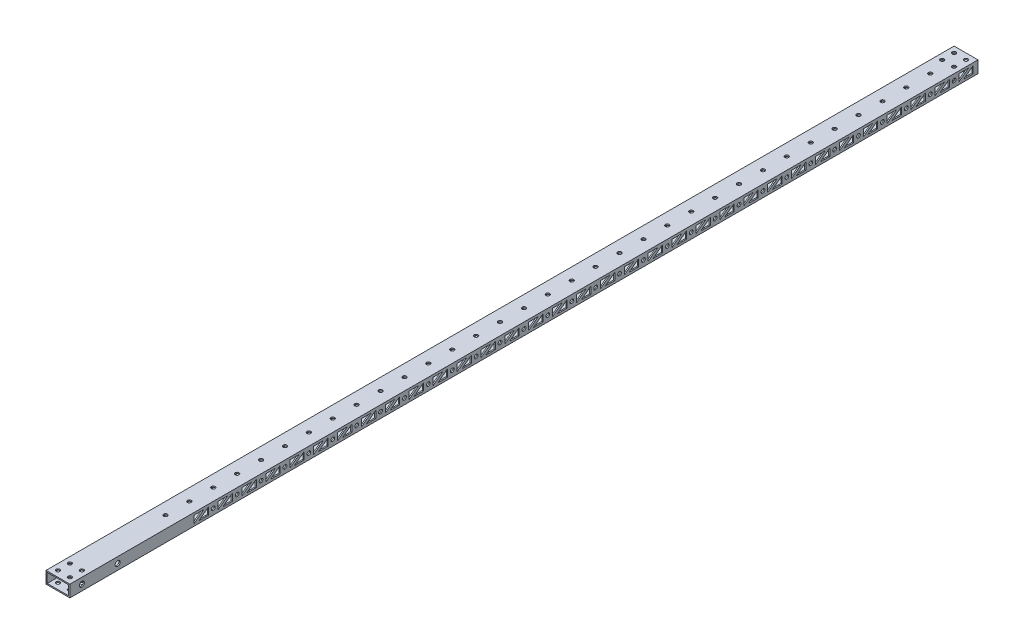
SolidWorks part; units mm, degrees
ref_plane "前视基准面" through (0, 0, 0) normal (0, 0, 1) x (1, 0, 0)
ref_plane "上视基准面" through (0, 0, 0) normal (0, 1, 0) x (1, 0, 0)
ref_plane "右视基准面" through (0, 0, 0) normal (1, 0, 0) x (0, 0, -1)
other "Configuration Table"
sketch "草图1" plane through (0, 0, 0) normal (0, 0, 1) x (1, 0, 0)
  line L1 (0, 0) -> (20, 0)
  line L2 (0, 0) -> (0, -10)
  line L3 (0, -10) -> (20, -10)
  line L4 (20, 0) -> (20, -10)
  dimension "D1" = 20
  dimension "D2" = 10
extrude "拉伸-薄壁1" add sketch "草图1" along normal blind 760 thin
sketch "草图2" plane through (0, -10, 0) normal (0, -1, 0) x (1, 0, 0)
  line L0 (20, 10) -> (0, 10) construction
  line L1 (20, 760) -> (20, 0) construction
  line L2 (0, 760) -> (0, 0) construction
  line L3 (10, 0) -> (10, 10) construction
  line L4 (0, 0) -> (20, 0) construction
  line L5 (10, 10) -> (10, 30) construction
  line L6 (0, 380) -> (20, 380) construction
  line L7 (10, 760) -> (10, 750) construction
  line L8 (20, 750) -> (0, 750) construction
  circle A0 centre (5, 5) radius 1.575
  circle A1 centre (15, 5) radius 1.575
  circle A2 centre (15, 15) radius 1.575
  circle A3 centre (5, 15) radius 1.575
  circle A4 centre (10, 30) radius 1.575
  circle A5 centre (10, 50) radius 1.575
  circle A6 centre (10, 70) radius 1.575
  circle A7 centre (10, 90) radius 1.575
  circle A8 centre (10, 110) radius 1.575
  circle A9 centre (10, 130) radius 1.575
  circle A10 centre (10, 150) radius 1.575
  circle A11 centre (10, 170) radius 1.575
  circle A12 centre (10, 190) radius 1.575
  circle A13 centre (10, 210) radius 1.575
  circle A14 centre (10, 230) radius 1.575
  circle A15 centre (10, 250) radius 1.575
  circle A16 centre (10, 270) radius 1.575
  circle A17 centre (10, 290) radius 1.575
  circle A18 centre (10, 310) radius 1.575
  circle A19 centre (10, 330) radius 1.575
  circle A20 centre (10, 350) radius 1.575
  circle A21 centre (10, 370) radius 1.575
  circle A22 centre (10, 390) radius 1.575
  circle A23 centre (10, 410) radius 1.575
  circle A24 centre (10, 430) radius 1.575
  circle A25 centre (10, 450) radius 1.575
  circle A26 centre (10, 470) radius 1.575
  circle A27 centre (10, 490) radius 1.575
  circle A28 centre (10, 510) radius 1.575
  circle A29 centre (10, 530) radius 1.575
  circle A30 centre (10, 550) radius 1.575
  circle A31 centre (10, 570) radius 1.575
  circle A32 centre (10, 590) radius 1.575
  circle A33 centre (10, 610) radius 1.575
  circle A37 centre (5, 745) radius 1.575
  circle A38 centre (15, 745) radius 1.575
  circle A39 centre (15, 755) radius 1.575
  circle A40 centre (5, 755) radius 1.575
  circle A41 centre (10, 630) radius 1.575
  circle A42 centre (10, 650) radius 1.575
  circle A43 centre (10, 670) radius 1.575
  dimension "D1" = 3.15
  dimension "D5" = 3.15
  dimension "D2" = 5
  dimension "D3" = 5
  dimension "D4" = 10
  dimension "D6" = 20
  dimension "D8" = 20
  dimension "D7" = 33
extrude "切除-拉伸1" cut sketch "草图2" against normal through all
sketch "草图4" plane through (20, 0, 0) normal (1, 0, 0) x (0, 0, -1)
  line L0 (0, -5) -> (-760, -5) construction
  line L1 (0, -10) -> (0, 0) construction
  line L2 (-760, -10) -> (-760, 0) construction
  line L3 (-4, -2) -> (-4, -8)
  line L4 (-4, -8) -> (-12, -8)
  line L5 (-12, -8) -> (-4, -2)
  line L6 (-8, -2) -> (-16, -8)
  line L7 (-16, -8) -> (-16, -2)
  line L8 (-16, -2) -> (-8, -2)
  line L9 (-760, -10) -> (0, -10) construction
  line L10 (-760, 0) -> (0, 0) construction
  line L11 (-24, -2) -> (-24, -8)
  line L12 (-24, -8) -> (-32, -8)
  line L13 (-32, -8) -> (-24, -2)
  line L14 (-36, -2) -> (-28, -2)
  line L15 (-28, -2) -> (-36, -8)
  line L16 (-36, -8) -> (-36, -2)
  line L17 (-44, -2) -> (-44, -8)
  line L18 (-44, -8) -> (-52, -8)
  line L19 (-52, -8) -> (-44, -2)
  line L20 (-56, -2) -> (-48, -2)
  line L21 (-48, -2) -> (-56, -8)
  line L22 (-56, -8) -> (-56, -2)
  line L23 (-64, -2) -> (-64, -8)
  line L24 (-64, -8) -> (-72, -8)
  line L25 (-72, -8) -> (-64, -2)
  line L26 (-76, -2) -> (-68, -2)
  line L27 (-68, -2) -> (-76, -8)
  line L28 (-76, -8) -> (-76, -2)
  line L29 (-84, -2) -> (-84, -8)
  line L30 (-84, -8) -> (-92, -8)
  line L31 (-92, -8) -> (-84, -2)
  line L32 (-96, -2) -> (-88, -2)
  line L33 (-88, -2) -> (-96, -8)
  line L34 (-96, -8) -> (-96, -2)
  line L35 (-104, -2) -> (-104, -8)
  line L36 (-104, -8) -> (-112, -8)
  line L37 (-112, -8) -> (-104, -2)
  line L38 (-116, -2) -> (-108, -2)
  line L39 (-108, -2) -> (-116, -8)
  line L40 (-116, -8) -> (-116, -2)
  line L41 (-124, -2) -> (-124, -8)
  line L42 (-124, -8) -> (-132, -8)
  line L43 (-132, -8) -> (-124, -2)
  line L44 (-136, -2) -> (-128, -2)
  line L45 (-128, -2) -> (-136, -8)
  line L46 (-136, -8) -> (-136, -2)
  line L47 (-144, -2) -> (-144, -8)
  line L48 (-144, -8) -> (-152, -8)
  line L49 (-152, -8) -> (-144, -2)
  line L50 (-156, -2) -> (-148, -2)
  line L51 (-148, -2) -> (-156, -8)
  line L52 (-156, -8) -> (-156, -2)
  line L53 (-164, -2) -> (-164, -8)
  line L54 (-164, -8) -> (-172, -8)
  line L55 (-172, -8) -> (-164, -2)
  line L56 (-176, -2) -> (-168, -2)
  line L57 (-168, -2) -> (-176, -8)
  line L58 (-176, -8) -> (-176, -2)
  line L59 (-184, -2) -> (-184, -8)
  line L60 (-184, -8) -> (-192, -8)
  line L61 (-192, -8) -> (-184, -2)
  line L62 (-196, -2) -> (-188, -2)
  line L63 (-188, -2) -> (-196, -8)
  line L64 (-196, -8) -> (-196, -2)
  line L65 (-204, -2) -> (-204, -8)
  line L66 (-204, -8) -> (-212, -8)
  line L67 (-212, -8) -> (-204, -2)
  line L68 (-216, -2) -> (-208, -2)
  line L69 (-208, -2) -> (-216, -8)
  line L70 (-216, -8) -> (-216, -2)
  line L71 (-224, -2) -> (-224, -8)
  line L72 (-224, -8) -> (-232, -8)
  line L73 (-232, -8) -> (-224, -2)
  line L74 (-236, -2) -> (-228, -2)
  line L75 (-228, -2) -> (-236, -8)
  line L76 (-236, -8) -> (-236, -2)
  line L77 (-244, -2) -> (-244, -8)
  line L78 (-244, -8) -> (-252, -8)
  line L79 (-252, -8) -> (-244, -2)
  line L80 (-256, -2) -> (-248, -2)
  line L81 (-248, -2) -> (-256, -8)
  line L82 (-256, -8) -> (-256, -2)
  line L83 (-264, -2) -> (-264, -8)
  line L84 (-264, -8) -> (-272, -8)
  line L85 (-272, -8) -> (-264, -2)
  line L86 (-276, -2) -> (-268, -2)
  line L87 (-268, -2) -> (-276, -8)
  line L88 (-276, -8) -> (-276, -2)
  line L89 (-284, -2) -> (-284, -8)
  line L90 (-284, -8) -> (-292, -8)
  line L91 (-292, -8) -> (-284, -2)
  line L92 (-296, -2) -> (-288, -2)
  line L93 (-288, -2) -> (-296, -8)
  line L94 (-296, -8) -> (-296, -2)
  line L95 (-304, -2) -> (-304, -8)
  line L96 (-304, -8) -> (-312, -8)
  line L97 (-312, -8) -> (-304, -2)
  line L98 (-316, -2) -> (-308, -2)
  line L99 (-308, -2) -> (-316, -8)
  line L100 (-316, -8) -> (-316, -2)
  line L101 (-324, -2) -> (-324, -8)
  line L102 (-324, -8) -> (-332, -8)
  line L103 (-332, -8) -> (-324, -2)
  line L104 (-336, -2) -> (-328, -2)
  line L105 (-328, -2) -> (-336, -8)
  line L106 (-336, -8) -> (-336, -2)
  line L107 (-344, -2) -> (-344, -8)
  line L108 (-344, -8) -> (-352, -8)
  line L109 (-352, -8) -> (-344, -2)
  line L110 (-356, -2) -> (-348, -2)
  line L111 (-348, -2) -> (-356, -8)
  line L112 (-356, -8) -> (-356, -2)
  line L113 (-364, -2) -> (-364, -8)
  line L114 (-364, -8) -> (-372, -8)
  line L115 (-372, -8) -> (-364, -2)
  line L116 (-376, -2) -> (-368, -2)
  line L117 (-368, -2) -> (-376, -8)
  line L118 (-376, -8) -> (-376, -2)
  line L119 (-384, -2) -> (-384, -8)
  line L120 (-384, -8) -> (-392, -8)
  line L121 (-392, -8) -> (-384, -2)
  line L122 (-396, -2) -> (-388, -2)
  line L123 (-388, -2) -> (-396, -8)
  line L124 (-396, -8) -> (-396, -2)
  line L125 (-404, -2) -> (-404, -8)
  line L126 (-404, -8) -> (-412, -8)
  line L127 (-412, -8) -> (-404, -2)
  line L128 (-416, -2) -> (-408, -2)
  line L129 (-408, -2) -> (-416, -8)
  line L130 (-416, -8) -> (-416, -2)
  line L131 (-424, -2) -> (-424, -8)
  line L132 (-424, -8) -> (-432, -8)
  line L133 (-432, -8) -> (-424, -2)
  line L134 (-436, -2) -> (-428, -2)
  line L135 (-428, -2) -> (-436, -8)
  line L136 (-436, -8) -> (-436, -2)
  line L137 (-444, -2) -> (-444, -8)
  line L138 (-444, -8) -> (-452, -8)
  line L139 (-452, -8) -> (-444, -2)
  line L140 (-456, -2) -> (-448, -2)
  line L141 (-448, -2) -> (-456, -8)
  line L142 (-456, -8) -> (-456, -2)
  line L143 (-464, -2) -> (-464, -8)
  line L144 (-464, -8) -> (-472, -8)
  line L145 (-472, -8) -> (-464, -2)
  line L146 (-476, -2) -> (-468, -2)
  line L147 (-468, -2) -> (-476, -8)
  line L148 (-476, -8) -> (-476, -2)
  line L149 (-484, -2) -> (-484, -8)
  line L150 (-484, -8) -> (-492, -8)
  line L151 (-492, -8) -> (-484, -2)
  line L152 (-496, -2) -> (-488, -2)
  line L153 (-488, -2) -> (-496, -8)
  line L154 (-496, -8) -> (-496, -2)
  line L155 (-504, -2) -> (-504, -8)
  line L156 (-504, -8) -> (-512, -8)
  line L157 (-512, -8) -> (-504, -2)
  line L158 (-516, -2) -> (-508, -2)
  line L159 (-508, -2) -> (-516, -8)
  line L160 (-516, -8) -> (-516, -2)
  line L161 (-524, -2) -> (-524, -8)
  line L162 (-524, -8) -> (-532, -8)
  line L163 (-532, -8) -> (-524, -2)
  line L164 (-536, -2) -> (-528, -2)
  line L165 (-528, -2) -> (-536, -8)
  line L166 (-536, -8) -> (-536, -2)
  line L167 (-544, -2) -> (-544, -8)
  line L168 (-544, -8) -> (-552, -8)
  line L169 (-552, -8) -> (-544, -2)
  line L170 (-556, -2) -> (-548, -2)
  line L171 (-548, -2) -> (-556, -8)
  line L172 (-556, -8) -> (-556, -2)
  line L173 (-564, -2) -> (-564, -8)
  line L174 (-564, -8) -> (-572, -8)
  line L175 (-572, -8) -> (-564, -2)
  line L176 (-576, -2) -> (-568, -2)
  line L177 (-568, -2) -> (-576, -8)
  line L178 (-576, -8) -> (-576, -2)
  line L179 (-584, -2) -> (-584, -8)
  line L180 (-584, -8) -> (-592, -8)
  line L181 (-592, -8) -> (-584, -2)
  line L182 (-596, -2) -> (-588, -2)
  line L183 (-588, -2) -> (-596, -8)
  line L184 (-596, -8) -> (-596, -2)
  line L185 (-604, -2) -> (-604, -8)
  line L186 (-604, -8) -> (-612, -8)
  line L187 (-612, -8) -> (-604, -2)
  line L188 (-616, -2) -> (-608, -2)
  line L189 (-608, -2) -> (-616, -8)
  line L190 (-616, -8) -> (-616, -2)
  line L191 (-624, -2) -> (-624, -8)
  line L192 (-624, -8) -> (-632, -8)
  line L193 (-632, -8) -> (-624, -2)
  line L194 (-636, -2) -> (-628, -2)
  line L195 (-628, -2) -> (-636, -8)
  line L196 (-636, -8) -> (-636, -2)
  line L197 (-644, -2) -> (-644, -8)
  line L198 (-644, -8) -> (-652, -8)
  line L199 (-652, -8) -> (-644, -2)
  line L200 (-656, -2) -> (-648, -2)
  line L201 (-648, -2) -> (-656, -8)
  line L202 (-656, -8) -> (-656, -2)
  line L215 (-664, -2) -> (-664, -8) [skipped]
  line L216 (-664, -8) -> (-672, -8) [skipped]
  line L217 (-672, -8) -> (-664, -2) [skipped]
  line L218 (-676, -2) -> (-668, -2) [skipped]
  line L219 (-668, -2) -> (-676, -8) [skipped]
  line L220 (-676, -8) -> (-676, -2) [skipped]
  line L221 (-684, -2) -> (-684, -8) [skipped]
  line L222 (-684, -8) -> (-692, -8) [skipped]
  line L223 (-692, -8) -> (-684, -2) [skipped]
  line L224 (-696, -2) -> (-688, -2) [skipped]
  line L225 (-688, -2) -> (-696, -8) [skipped]
  line L226 (-696, -8) -> (-696, -2) [skipped]
  circle A0 centre (-20, -5) radius 1.575
  circle A1 centre (-40, -5) radius 1.575
  circle A2 centre (-60, -5) radius 1.575
  circle A3 centre (-80, -5) radius 1.575
  circle A4 centre (-100, -5) radius 1.575
  circle A5 centre (-120, -5) radius 1.575
  circle A6 centre (-140, -5) radius 1.575
  circle A7 centre (-160, -5) radius 1.575
  circle A8 centre (-180, -5) radius 1.575
  circle A9 centre (-200, -5) radius 1.575
  circle A10 centre (-220, -5) radius 1.575
  circle A11 centre (-240, -5) radius 1.575
  circle A12 centre (-260, -5) radius 1.575
  circle A13 centre (-280, -5) radius 1.575
  circle A14 centre (-300, -5) radius 1.575
  circle A15 centre (-320, -5) radius 1.575
  circle A16 centre (-340, -5) radius 1.575
  circle A17 centre (-360, -5) radius 1.575
  circle A18 centre (-380, -5) radius 1.575
  circle A19 centre (-400, -5) radius 1.575
  circle A20 centre (-420, -5) radius 1.575
  circle A21 centre (-440, -5) radius 1.575
  circle A22 centre (-460, -5) radius 1.575
  circle A23 centre (-480, -5) radius 1.575
  circle A24 centre (-500, -5) radius 1.575
  circle A25 centre (-520, -5) radius 1.575
  circle A26 centre (-540, -5) radius 1.575
  circle A27 centre (-560, -5) radius 1.575
  circle A28 centre (-580, -5) radius 1.575
  circle A29 centre (-600, -5) radius 1.575
  circle A30 centre (-620, -5) radius 1.575
  circle A31 centre (-640, -5) radius 1.575
  circle A36 centre (-660, -5) radius 1.575 [skipped]
  circle A37 centre (-680, -5) radius 1.575 [skipped]
  circle A38 centre (-750, -5) radius 2.1
  circle A39 centre (-720, -5) radius 2.1
  point P84 (0, 0)
  dimension "D2" = 3.15
  dimension "D13" = 10
  dimension "D15" = 4.2
  dimension "D14" = 4.2
  dimension "D1" = 20
  dimension "D3" = 20
  dimension "D4" = 8
  dimension "D5" = 6
  dimension "D6" = 6
  dimension "D7" = 2
  dimension "D8" = 2
  dimension "D9" = 12
  dimension "D10" = 4
  dimension "D12" = 20
  dimension "D16" = 30
  dimension "D11" = 35
extrude "切除-拉伸2" cut sketch "草图4" against normal through all
